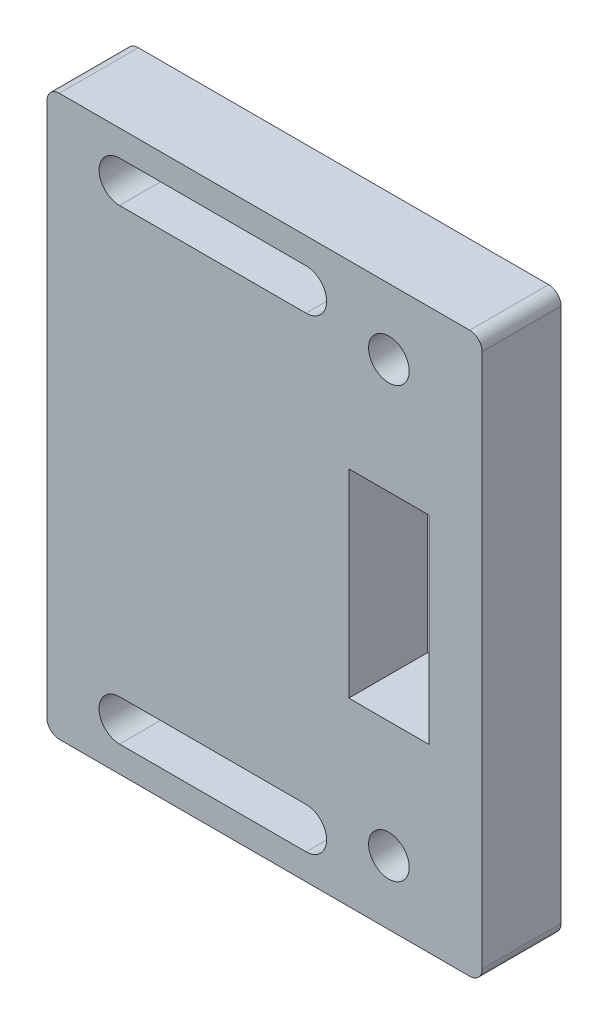
SolidWorks part; units mm, degrees
ref_plane "Front Plane" through (0, 0, 0) normal (0, 0, 1) x (1, 0, 0)
ref_plane "Top Plane" through (0, 0, 0) normal (0, 1, 0) x (1, 0, 0)
ref_plane "Right Plane" through (0, 0, 0) normal (1, 0, 0) x (0, 0, -1)
sketch "Sketch1" plane through (0, 0, 0) normal (0, 0, 1) x (1, 0, 0)
  line L0 (70, -45) -> (0, -45) construction
  line L1 (0, 0) -> (70, 0)
  line L2 (0, 0) -> (0, -90)
  line L3 (0, -90) -> (70, -90)
  line L4 (70, 0) -> (70, -90)
  line L5 (55, -45) -> (55, -29.025) construction
  line L6 (55, -29.025) -> (61.45, -29.025)
  line L7 (61.45, -29.025) -> (61.45, -60.975)
  line L8 (61.45, -60.975) -> (55, -60.975)
  line L9 (55, -60.975) -> (48.55, -60.975)
  line L10 (48.55, -60.975) -> (48.55, -29.025)
  line L11 (48.55, -29.025) -> (55, -29.025)
  line L12 (55, -45) -> (55, -60.975) construction
  line L13 (55, 0) -> (55, -13.25) construction
  line L14 (55, -90) -> (55, -79.56) construction
  dimension "D1" = 90
  dimension "D2" = 55
  dimension "D3" = 12.9
  dimension "D4" = 31.95
  dimension "D5" = 70
  dimension "D6" = 10.44
  dimension "D7" = 55
  dimension "D8" = 55
  dimension "D9" = 29.025
extrude "Boss-Extrude1" add sketch "Sketch1" along normal blind 12.7
sketch "Sketch4" plane through (0, 0, 0) normal (0, 0, -1) x (-1, 0, 0)
  line L0 (-55, -0.2792) -> (-55, -10.5796)
  line L2 (-55, -90) -> (-55, -79.6996)
  line L4 (-55, -79.6996) -> (-55, -10.5796) construction
  line L5 (0, 0) -> (0, -90) construction
  line L6 (0, -90) -> (-70, -90) construction
  line L9 (0, -90) -> (-70, -90) construction
  dimension "D1" = 55
  dimension "D2" = 10.3004
  dimension "D3" = 69.12
hole_wizard "CSK for 1/4 Flat Head Machine Screw1" positions "Sketch5" profile "Sketch6" countersink size "1/4" standard "ANSI Inch" end condition through all
sketch "Sketch5" plane through (0, 0, 0) normal (0, 0, -1) x (-1, 0, 0)
  point P0 (-55, -10.5796)
  point P3 (-55, -79.6996)
sketch "Sketch6" plane through (55, -10.5796, 0) normal (1, 0, 0) x (0, 1, 0)
  line L0 (0, 0) -> (0, 12.7)
  line L1 (0, 12.7) -> (3.2639, 12.7)
  line L2 (3.2639, 12.7) -> (3.2639, 3.6524)
  line L3 (3.2639, 3.6524) -> (6.4389, 0)
  line L5 (6.4389, 0) -> (0, 0)
  line L6 (-3.2639, 3.6524) -> (-6.4389, 0) construction
  line L11 (0, -6.35) -> (0, 107.95) construction
  dimension "Thru Hole Dia." = 6.5278
  dimension "Thru Hole Depth" = 12.7
  dimension "Near C'Sink Dia." = 12.8778
  dimension "Near C'Sink Angle" = 82
fillet "Fillet1" radius 2 4 edges at (0, 0, 6.35) (70, 0, 6.35) (0, -90, 6.35) (70, -90, 6.35)
sketch "Sketch7" plane through (0, 0, 0) normal (0, 0, -1) x (-1, 0, 0)
  line L0 (-41.6875, -85.815) -> (-11.6875, -85.815)
  line L1 (-11.6875, -79.215) -> (-41.6875, -79.215)
  line L2 (-11.6875, -79.215) -> (-11.6875, -10.785) construction
  line L3 (-11.6875, -10.785) -> (-41.6875, -10.785)
  line L4 (-11.6875, -4.185) -> (-41.6875, -4.185)
  line L5 (-26.6875, -85.815) -> (-26.6875, -90) construction
  line L6 (-2, -90) -> (-68, -90) construction
  line L7 (-26.6875, -4.185) -> (-26.6875, 0) construction
  line L8 (-70, -45) -> (-43.27, -45) construction
  line L9 (-70, -88) -> (-70, -2) construction
  line L10 (-11.6875, -82.515) -> (0, -82.515) construction
  line L11 (0, -2) -> (0, -88) construction
  line L12 (-68, 0) -> (-2, 0) construction
  line L13 (-11.6875, -7.485) -> (0, -7.485) construction
  arc A0 (-11.6875, -85.815) -> (-11.6875, -79.215) centre (-11.6875, -82.515) ccw
  arc A1 (-41.6875, -79.215) -> (-41.6875, -85.815) centre (-41.6875, -82.515) ccw
  arc A2 (-11.6875, -10.785) -> (-11.6875, -4.185) centre (-11.6875, -7.485) ccw
  arc A3 (-41.6875, -4.185) -> (-41.6875, -10.785) centre (-41.6875, -7.485) ccw
  dimension "D1" = 3.3
  dimension "D4" = 3.3
  dimension "D2" = 30
  dimension "D3" = 68.43
  dimension "D5" = 30
  dimension "D6" = 11.6875
extrude "Cut-Extrude1" cut sketch "Sketch7" against normal through all contours A1 L0 A0 L1 | A3 L3 A2 L4
